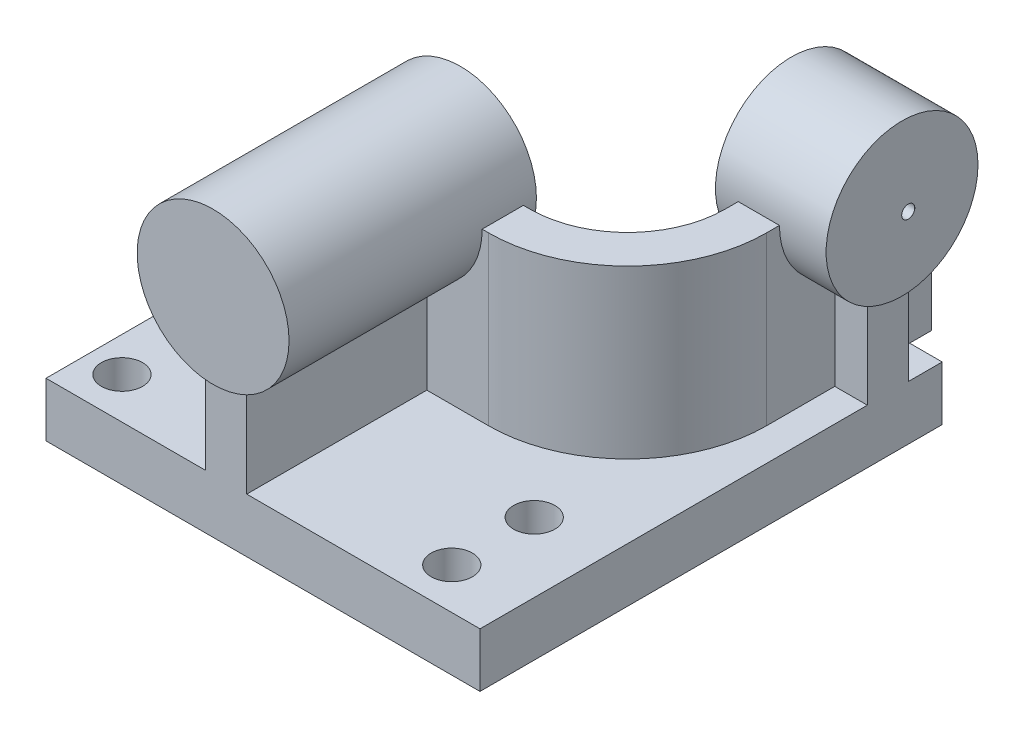
SolidWorks part; units mm, degrees
ref_plane "Front Plane" through (0, 0, 0) normal (0, 0, 1) x (1, 0, 0)
ref_plane "Top Plane" through (0, 0, 0) normal (0, 1, 0) x (1, 0, 0)
ref_plane "Right Plane" through (0, 0, 0) normal (1, 0, 0) x (0, 0, -1)
sketch "Sketch1" plane through (0, 0, 0) normal (0, 1, 0) x (1, 0, 0)
  line L0 (0, 0) -> (0, -70645.5278) construction
  line L1 (0, 0) -> (-70645.5278, 0) construction
  line L2 (0, 102) -> (0, 0)
  line L3 (0, 0) -> (200, 0)
  line L4 (200, 0) -> (200, 213)
  line L5 (200, 213) -> (166, 213)
  line L6 (166, 213) -> (166, 147)
  line L7 (121, 102) -> (0, 102)
  arc A0 (166, 147) -> (121, 102) centre (121, 147) cw
  circle A1 centre (16, 57) radius 9.5
  circle A2 centre (16, 19) radius 9.5
  circle A3 centre (168, 19) radius 9.5
  circle A4 centre (168, 57) radius 9.5
  point P21 (0, 0)
  point P22 (0, 0)
  point P23 (-42.8746, 224.8702)
  point P24 (0, 0)
  point P25 (0, 0)
  dimension "D5" = 45
  dimension "D6" = 19
  dimension "D1" = 102
  dimension "D2" = 200
  dimension "D3" = 34
  dimension "D4" = 213
  dimension "D7" = 38
  dimension "D8" = 152
  dimension "D9" = 19
  dimension "D10" = 32
extrude "Boss-Extrude1" add sketch "Sketch1" along normal blind 25
sketch "Sketch2" plane through (0, 0, 0) normal (0, 0, 1) x (1, 0, 0)
  line L0 (0, 25) -> (0, 0) construction
  line L1 (0, 0) -> (200, 0) construction
  circle A0 centre (83, 102) radius 35
  dimension "D1" = 70
  dimension "D2" = 83
  dimension "D3" = 102
extrude "Boss-Extrude2" add sketch "Sketch2" along normal blind 6 and the other way blind 108 separate body
sketch "Sketch3" plane through (200, 0, 0) normal (1, 0, 0) x (0, 0, -1)
  line L0 (213, 25) -> (213, 0) construction
  line L1 (0, 0) -> (213, 0) construction
  circle A0 centre (188, 102) radius 35
  point P6 (0, 0)
  dimension "D1" = 70
  dimension "D2" = 25
  dimension "D3" = 102
extrude "Boss-Extrude3" add sketch "Sketch3" along normal blind 6.5 and the other way blind 44.5 separate body contours A0
sketch "Sketch4" plane through (0, 25, 0) normal (0, 1, 0) x (1, 0, 0)
  line L0 (121, 102) -> (0, 102) construction
  line L1 (166, 213) -> (166, 147) construction
  line L2 (121, 102) -> (48, 102)
  line L3 (166, 223) -> (166, 147)
  line L4 (185, 223) -> (185, 147)
  line L5 (121, 83) -> (48, 83)
  line L6 (166, 213) -> (166, 147) construction
  line L7 (185, 213) -> (185, 147) construction
  line L8 (206.5, 223) -> (155.5, 223) construction
  line L9 (166, 223) -> (185, 223)
  line L10 (48, 108) -> (48, -6) construction
  line L11 (48, 102) -> (48, 83)
  line L12 (121, 102) -> (0, 102) construction
  line L13 (121, 83) -> (0, 83) construction
  arc A0 (121, 102) -> (166, 147) centre (121, 147) ccw construction
  arc A1 (121, 102) -> (166, 147) centre (121, 147) ccw
  arc A2 (121, 83) -> (185, 147) centre (121, 147) ccw
  dimension "D1" = 19
extrude "Boss-Extrude4" add sketch "Sketch4" along normal blind 77
sketch "Sketch5" plane through (200, 0, 0) normal (1, 0, 0) x (0, 0, -1)
  line L0 (188, 59.7395) -> (188, 34.8152)
  line L1 (223, 102) -> (223, 25) construction
  point P4 (188, -18.4882)
  point P5 (188, 34.8152)
  dimension "D1" = 35
rib "Rib1" sketch "Sketch5" sketch "Sketch5" thickness 19 extrusion direction normal to sketch draft on no parameters "D1"=19
sketch "Sketch6" plane through (0, 0, 0) normal (0, 0, 1) x (1, 0, 0)
  line L0 (83, 58.1524) -> (83, 30.1138)
  line L1 (0, 25) -> (0, 0) construction
  dimension "D1" = 83
rib "Rib2" sketch "Sketch6" sketch "Sketch6" thickness 19 extrusion direction normal to sketch draft on no parameters "D1"=19
hole_wizard "Ø6.0mm Dowel Hole1" positions "3DSketch3" profile "Sketch11" hole size "Ø6.0" standard "ISO"
sketch3d "3DSketch3"
  point P0 (206.5, 99.3197, -190.8633)
sketch "Sketch11" plane through (206.5, 99.3197, -190.8633) normal (0, 1, 0) x (0, 0, -1)
  line L0 (0, 0) -> (0, 55.8026)
  line L1 (0, 55.8026) -> (3, 54)
  line L2 (3, 54) -> (3, 0.025)
  line L3 (3, 0.025) -> (3.025, 0)
  line L5 (3.025, 0) -> (0, 0)
  line L6 (-3, 0.025) -> (-3.025, 0) construction
  line L10 (0, 55.8026) -> (-3, 54) construction
  line L11 (0, -6.35) -> (0, 107.95) construction
  dimension "Hole Dia." = 6
  dimension "Hole Depth" = 54
  dimension "Near C'Sink Dia." = 6.05
  dimension "Near C'Sink Angle" = 90
  dimension "Drill Angle" = 118
